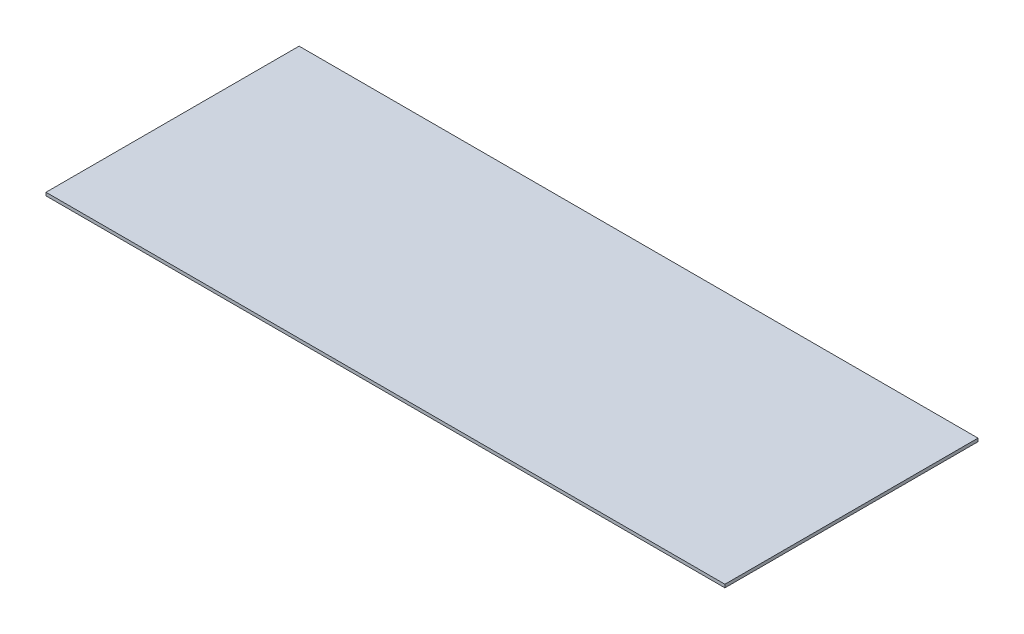
SolidWorks part; units mm, degrees
ref_plane "Alzado" through (0, 0, 0) normal (0, 0, 1) x (1, 0, 0)
ref_plane "Planta" through (0, 0, 0) normal (0, 1, 0) x (1, 0, 0)
ref_plane "Vista lateral" through (0, 0, 0) normal (1, 0, 0) x (0, 0, -1)
sketch "Croquis1" plane through (0, 0, 0) normal (0, 1, 0) x (1, 0, 0)
  line L1 (536.5, -200) -> (-536.5, -200)
  line L2 (536.5, -200) -> (536.5, 200)
  line L3 (536.5, 200) -> (-536.5, 200)
  line L4 (-536.5, -200) -> (-536.5, 200)
  line L5 (536.5, -200) -> (-536.5, 200) construction
  line L6 (536.5, 200) -> (-536.5, -200) construction
  point P0 (0, 0)
  dimension "D1" = 1073
  dimension "D2" = 400
extrude "Extruir1" add sketch "Croquis1" along normal blind 5
